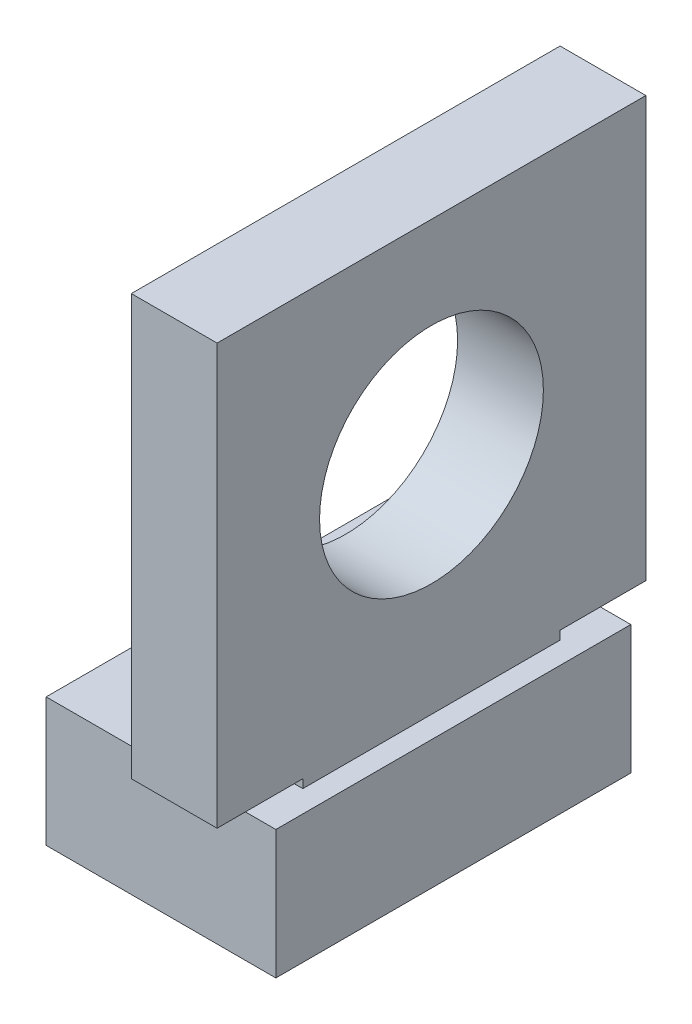
SolidWorks part; units mm, degrees
ref_plane "Front Plane" through (0, 0, 0) normal (0, 0, 1) x (1, 0, 0)
ref_plane "Top Plane" through (0, 0, 0) normal (0, 1, 0) x (1, 0, 0)
ref_plane "Right Plane" through (0, 0, 0) normal (1, 0, 0) x (0, 0, -1)
sketch "Sketch1" plane through (0, 0, 0) normal (0, 1, 0) x (1, 0, 0)
  line L1 (-140, 105) -> (140, 105)
  line L2 (-140, 105) -> (-140, -105)
  line L3 (-140, -105) -> (140, -105)
  line L4 (140, 105) -> (140, -105)
  line L5 (-140, 105) -> (140, -105) construction
  line L6 (-140, -105) -> (140, 105) construction
  point P0 (0, 0)
  dimension "D1" = 280
  dimension "D2" = 210
extrude "Boss-Extrude1" add sketch "Sketch1" along normal blind 15
sketch "Sketch2" plane through (0, 15, 0) normal (0, 1, 0) x (1, 0, 0)
  line L0 (-105, 0) -> (-100, 0) construction
  line L2 (-100, 0) -> (-95, 0) construction
  line L3 (-100, 0) -> (-100, 5) construction
  line L4 (-100, 0) -> (-100, -5) construction
  line L5 (-75, 0) -> (-62.5, 0) construction
  line L6 (-100, -40) -> (-100, -45) construction
  line L7 (-100, 40) -> (-100, 45) construction
  circle A3 centre (-100, 0) radius 5
  circle A4 centre (-100, 45) radius 5
  circle A5 centre (-100, -45) radius 5
  dimension "D3" = 45
  dimension "D4" = 45
  dimension "D2" = 37.5
extrude "Boss-Extrude2" add sketch "Sketch2" along normal blind 50
sketch "Sketch3" plane through (0, 15, 0) normal (0, 1, 0) x (1, 0, 0)
  line L1 (5, 15) -> (-5, 15)
  line L2 (5, 15) -> (5, -15)
  line L3 (5, -15) -> (-5, -15)
  line L4 (-5, 15) -> (-5, -15)
  line L5 (5, 15) -> (-5, -15) construction
  line L6 (5, -15) -> (-5, 15) construction
  point P0 (0, 0)
extrude "Boss-Extrude3" add sketch "Sketch3" along normal up to surface (50 mm away) up to face at (-100, 65, 50)
sketch "Sketch4" plane through (5, 0, 0) normal (1, 0, 0) x (0, 0, -1)
  circle A0 centre (0, 41.2362) radius 13.05
  dimension "D1" = 26.1
sketch "Sketch5" plane through (0, 0, 0) normal (0, 1, 0) x (1, 0, 0)
  line L1 (124.0869, 62.5479) -> (-124.0869, 62.5479)
  line L2 (124.0869, 62.5479) -> (124.0869, -62.5479)
  line L3 (124.0869, -62.5479) -> (-124.0869, -62.5479)
  line L4 (-124.0869, 62.5479) -> (-124.0869, -62.5479)
  line L7 (-178.9003, 121.3967) -> (181.5906, 121.3967)
  line L8 (-178.9003, 121.3967) -> (-178.9003, -127.786)
  line L9 (-178.9003, -127.786) -> (181.5906, -127.786)
  line L10 (181.5906, 121.3967) -> (181.5906, -127.786)
  line L11 (-124.0869, 62.5479) -> (124.0869, 62.5479)
  line L13 (-124.0869, 121.3967) -> (181.5906, 121.3967)
  line L14 (181.5906, 62.5479) -> (181.5906, 121.3967)
  line L17 (-124.0869, 121.3967) -> (-178.9003, 121.3967)
  line L18 (-178.9003, 62.5479) -> (-178.9003, 121.3967)
  line L20 (-178.9003, 62.5479) -> (-178.9003, -127.786)
  line L21 (-178.9003, -127.786) -> (-124.0869, -127.786)
  line L22 (-124.0869, 62.5479) -> (-124.0869, -62.5479)
  line L23 (-124.0869, -62.5479) -> (124.0869, -62.5479)
  line L25 (-124.0869, -127.786) -> (181.5906, -127.786)
  line L26 (181.5906, -62.5479) -> (181.5906, -127.786)
  line L28 (124.0869, 62.5479) -> (124.0869, -62.5479)
  line L30 (181.5906, 62.5479) -> (181.5906, -62.5479)
  point P0 (0, 0)
sketch "Sketch6" plane through (0, 0, 0) normal (0, 1, 0) x (1, 0, 0)
extrude "Cut-Extrude5" cut sketch "Sketch5" along normal up to surface (15 mm away) contours L10 L7 L8 L9 L4 L1 L2 L3 up to face at (-100, 15, 50)
sketch "Sketch7" plane through (0, 65, 0) normal (0, 1, 0) x (1, 0, 0)
  circle A0 centre (-100, 45) radius 5
  circle A1 centre (-100, 0) radius 5
  circle A2 centre (-100, -45) radius 5
extrude "Cut-Extrude6" cut sketch "Sketch7" against normal up to surface (65 mm away) up to face at (0, 0, 0)
sketch "Sketch8" plane through (0, 0, 0) normal (0, -1, 0) x (1, 0, 0)
  circle A0 centre (-100, 45) radius 10
  circle A1 centre (-100, 0) radius 10
  circle A2 centre (-100, -45) radius 10
extrude "Cut-Extrude7" cut sketch "Sketch8" against normal blind 12
sketch "Sketch9" plane through (0, 15, 0) normal (0, 1, 0) x (1, 0, 0)
  line L0 (-33.8328, 59.6319) -> (-62.9628, 59.6319)
  line L1 (-33.8328, 59.6319) -> (-33.8328, 42.9119)
  line L2 (-33.8328, 42.9119) -> (-62.9628, 42.9119)
  line L3 (-62.9628, 59.6319) -> (-62.9628, 42.9119)
  line L4 (-33.8328, 59.6319) -> (-62.9628, 42.9119) construction
  line L5 (-33.8328, 42.9119) -> (-62.9628, 59.6319) construction
  point P0 (-48.3978, 51.2719)
extrude "Cut-Extrude8" cut sketch "Sketch9" against normal blind 15
sketch "Sketch10" plane through (0, 15, 0) normal (0, 1, 0) x (1, 0, 0)
  line L0 (10.618, 62.5479) -> (-124.0869, 62.5479)
  line L4 (-124.0869, 62.5479) -> (-124.0869, -62.5479)
  line L10 (10.618, 62.5479) -> (124.0869, 62.5479)
  line L12 (10.618, -62.5479) -> (124.0869, -62.5479)
  line L13 (124.0869, 62.5479) -> (124.0869, -62.5479)
  line L15 (10.618, -62.5479) -> (-124.0869, -62.5479)
  line L18 (7.5501, -20.6978) -> (-19.2345, -20.6978)
  line L19 (-19.2345, 20.6978) -> (-19.2345, -20.6978)
  line L28 (-19.2345, 20.6978) -> (7.5501, 20.6978)
  line L29 (7.5501, 20.6978) -> (7.5501, -20.6978)
  point P16 (0, 0)
extrude "Cut-Extrude9" cut sketch "Sketch10" against normal blind 27
sketch "Sketch11" plane through (0, 0, -15) normal (0, 0, -1) x (-1, 0, 0)
  line L0 (-5, 16) -> (5, 16)
  line L1 (-7.5501, 15) -> (19.2345, 15) construction
  line L4 (5, 65) -> (-5, 65)
  line L5 (-5, 65) -> (-5, 15)
  line L6 (-5, 15) -> (5, 15)
  line L7 (5, 15) -> (5, 65)
  line L8 (5, 65) -> (-5, 65)
  line L9 (-5, 65) -> (-5, 16)
  line L11 (5, 16) -> (5, 65)
  dimension "D2" = 1
  dimension "D1" = 0
extrude "Boss-Extrude4" add sketch "Sketch11" along normal blind 10
sketch "Sketch12" plane through (0, 0, 15) normal (0, 0, 1) x (1, 0, 0)
  line L0 (-5, 16) -> (5, 16)
  line L1 (-5, 15) -> (5, 15) construction
  line L4 (5, 65) -> (-5, 65)
  line L5 (-5, 65) -> (-5, 15)
  line L6 (-5, 15) -> (5, 15)
  line L7 (5, 15) -> (5, 65)
  line L8 (5, 65) -> (-5, 65)
  line L9 (-5, 65) -> (-5, 16)
  line L11 (5, 16) -> (5, 65)
  dimension "D2" = 1
  dimension "D1" = 0
extrude "Boss-Extrude5" add sketch "Sketch12" along normal blind 10
extrude "Cut-Extrude10" cut sketch "Sketch4" against normal through all
